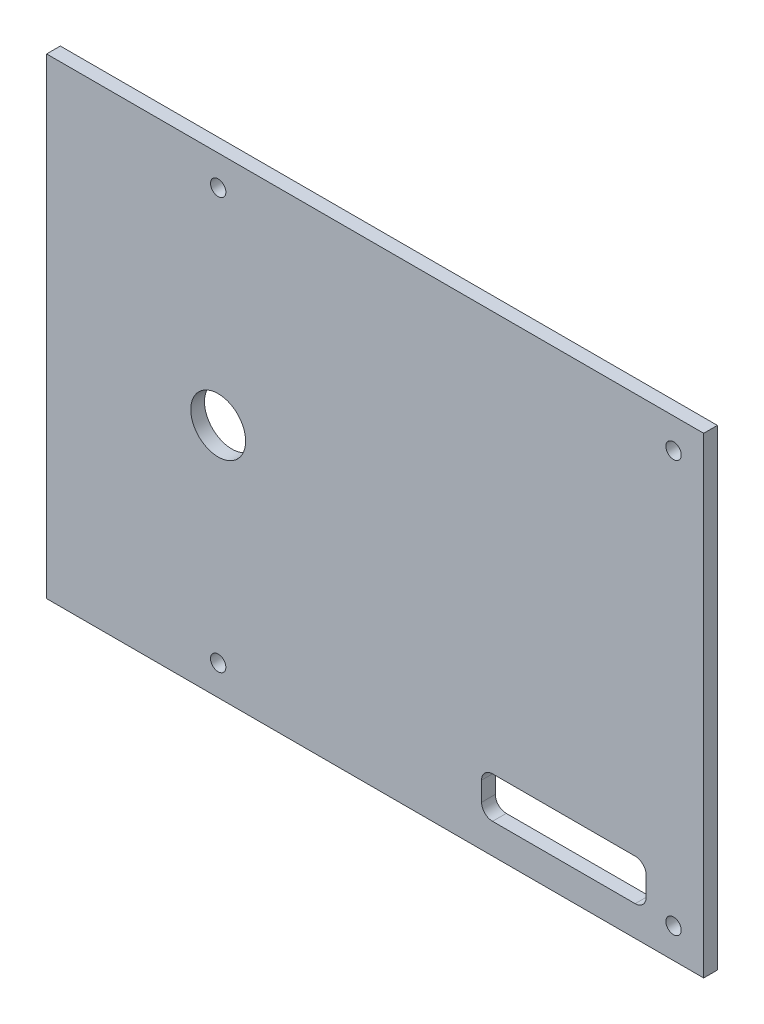
SolidWorks part; units mm, degrees
ref_plane "Front Plane" through (0, 0, 0) normal (0, 0, 1) x (1, 0, 0)
ref_plane "Top Plane" through (0, 0, 0) normal (0, 1, 0) x (1, 0, 0)
ref_plane "Right Plane" through (0, 0, 0) normal (1, 0, 0) x (0, 0, -1)
sketch "Sketch1" plane through (0, 0, 0) normal (0, 0, 1) x (1, 0, 0)
  line L0 (56.515, 51.435) -> (36.515, 51.435)
  line L1 (-56.515, -51.435) -> (56.515, -51.435)
  line L2 (-56.515, -51.435) -> (-56.515, 51.435)
  line L3 (-56.515, 51.435) -> (56.515, 51.435)
  line L4 (56.515, -51.435) -> (56.515, 51.435)
  line L5 (-56.515, -51.435) -> (56.515, 51.435) construction
  line L6 (-56.515, 51.435) -> (56.515, -51.435) construction
  line L7 (36.515, 51.435) -> (36.515, 42.935)
  line L8 (36.515, 42.935) -> (49.515, 42.935)
  line L9 (49.515, 42.935) -> (49.515, 47.935)
  line L10 (49.515, 47.935) -> (-71.485, 47.935)
  line L11 (-71.485, 47.935) -> (-71.485, -28.065)
  line L12 (-71.485, -28.065) -> (49.515, -28.065)
  line L13 (49.515, -28.065) -> (49.515, 47.935)
  line L14 (-71.485, 9.935) -> (-89.265, 9.935)
  line L15 (-89.265, 9.935) -> (-89.265, 51.435)
  line L16 (-89.265, 51.435) -> (-89.265, 54.61)
  line L17 (-89.265, 54.61) -> (56.515, 54.61)
  line L18 (56.515, 54.61) -> (59.69, 54.61)
  line L19 (59.69, 54.61) -> (59.69, -51.435)
  line L21 (0, -54.61) -> (59.69, -54.61)
  line L22 (59.69, -54.61) -> (59.69, -51.435)
  line L24 (0, -54.61) -> (-89.265, -54.61)
  line L25 (-89.265, -54.61) -> (-89.265, 9.935)
  circle A0 centre (-52.715, 47.635) radius 1.778
  circle A1 centre (52.715, 47.635) radius 1.778
  circle A2 centre (-52.715, -47.635) radius 1.778
  circle A3 centre (52.715, -47.635) radius 1.778
  point P0 (0, 0)
extrude "Boss-Extrude1" add sketch "Sketch1" along normal blind 3.175
sketch "Sketch2" plane through (0, 0, 3.175) normal (0, 0, 1) x (1, 0, 0)
  line L3 (46.365, -47.635) -> (46.365, -38.11)
  line L4 (46.365, -38.11) -> (8.265, -38.11)
  line L5 (8.265, -38.11) -> (8.265, -47.635)
  line L6 (8.265, -47.635) -> (46.365, -47.635)
extrude "Cut-Extrude1" cut sketch "Sketch2" against normal through all
fillet "Fillet1" radius 2.54 4 edges at (46.365, -47.635, 1.5875) (46.365, -38.11, 1.5875) (8.265, -38.11, 1.5875) (8.265, -47.635, 1.5875)
sketch "Sketch3" plane through (0, 0, 3.175) normal (0, 0, 1) x (1, 0, 0)
  circle A0 centre (-52.715, 0) radius 6.35
extrude "Cut-Extrude2" cut sketch "Sketch3" against normal through all
sketch "Sketch4" plane through (-89.265, 0, 0) normal (-1, 0, 0) x (0, 0, 1)
  line L1 (0, 54.61) -> (3.175, 54.61)
  line L2 (0, 54.61) -> (0, -54.61)
  line L3 (0, -54.61) -> (3.175, -54.61)
  line L4 (3.175, 54.61) -> (3.175, -54.61)
extrude "Boss-Extrude2" add sketch "Sketch4" along normal blind 3.175
